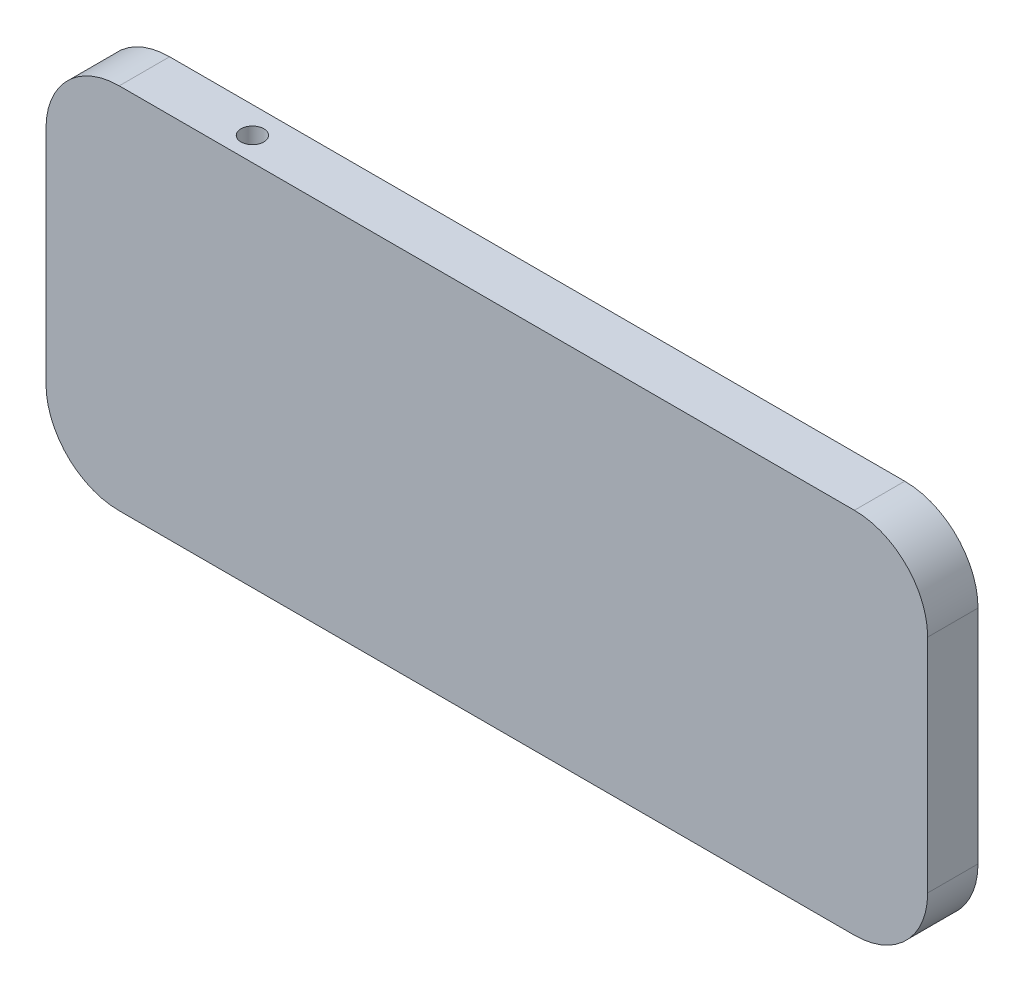
SolidWorks part; units mm, degrees
ref_plane "Front Plane" through (0, 0, 0) normal (0, 0, 1) x (1, 0, 0)
ref_plane "Top Plane" through (0, 0, 0) normal (0, 1, 0) x (1, 0, 0)
ref_plane "Right Plane" through (0, 0, 0) normal (1, 0, 0) x (0, 0, -1)
sketch "Sketch1" plane through (0, 0, 0) normal (0, 0, 1) x (1, 0, 0)
  line L1 (-43.0173, 84.2239) -> (160.9447, 84.2239)
  line L2 (-63.3373, 63.9039) -> (-63.3373, 2.4359)
  line L3 (-43.0173, -17.8841) -> (160.9447, -17.8841)
  line L4 (181.2647, 63.9039) -> (181.2647, 2.4359)
  line L5 (-27.5233, 84.2239) -> (-27.5233, -17.8841)
  line L7 (145.4507, 84.2239) -> (145.4507, -17.8841)
  arc A0 (-63.3373, 63.9039) -> (-43.0173, 84.2239) centre (-43.0173, 63.9039) cw
  arc A1 (-63.3373, 2.4359) -> (-43.0173, -17.8841) centre (-43.0173, 2.4359) ccw
  arc A2 (181.2647, 63.9039) -> (160.9447, 84.2239) centre (160.9447, 63.9039) ccw
  arc A3 (160.9447, -17.8841) -> (181.2647, 2.4359) centre (160.9447, 2.4359) ccw
  point P10 (-63.3373, 84.2239)
  point P13 (-63.3373, -17.8841)
  point P16 (181.2647, 84.2239)
  dimension "D5" = 20.32
  dimension "D6" = 20.32
  dimension "D7" = 20.32
  dimension "D8" = 20.32
  dimension "D1" = 244.602
  dimension "D2" = 102.108
  dimension "D3" = 35.814
  dimension "D4" = 35.814
extrude "Boss-Extrude1" add sketch "Sketch1" along normal blind 13.97 contours L7 L1 L5 L3 | L2 A1 L3 L5 L1 A0 | L3 A3 L4 A2 L1 L7
sketch "Sketch2" plane through (0, 0, 0) normal (0, 0, -1) x (-1, 0, 0)
  line L0 (-145.4507, 84.2239) -> (-145.4507, -17.8841)
  line L1 (43.0173, 84.2239) -> (-160.9447, 84.2239) construction
  line L2 (43.0173, -17.8841) -> (-160.9447, -17.8841) construction
  line L3 (-181.2647, 63.9039) -> (-181.2647, 2.4359) construction
  line L5 (-156.6365, 76.06) -> (-148.8243, 76.06)
  line L6 (-156.6365, 76.06) -> (-156.6365, 73.6521)
  line L7 (-156.6365, 73.6521) -> (-148.8243, 73.6521)
  line L8 (-148.8243, 76.06) -> (-148.8243, 73.6521)
  circle A0 centre (-163.4847, 58.8239) radius 7.4676
  circle A1 centre (-170.3371, 26.676) radius 3.015
  circle A2 centre (-163.2212, 32.8237) radius 3.015
  circle A3 centre (-156.7324, 26.2052) radius 3.015
  circle A4 centre (-163.7215, 19.9736) radius 3.015
  dimension "D2" = 17.78
  dimension "D1" = 35.814
  dimension "D3" = 25.4
extrude "Boss-Extrude3" add sketch "Sketch2" along normal blind 3.048 contours A3 | A2 | A4 | A1 | A0 | L6 L7 L8 L5
sketch "Sketch3" plane through (0, 0, 0) normal (0, 0, -1) x (-1, 0, 0)
  line L0 (27.7773, 84.2239) -> (27.7773, -17.8841)
  line L1 (43.0173, 84.2239) -> (-160.9447, 84.2239) construction
  line L2 (43.0173, -17.8841) -> (-160.9447, -17.8841) construction
  line L3 (63.3373, 63.9039) -> (63.3373, 2.4359) construction
  line L4 (35.9334, 76.3914) -> (35.9334, 78.9314)
  line L6 (33.5703, 76.3914) -> (33.5703, 73.9836)
  line L8 (41.1903, 76.3914) -> (41.1903, 73.9836)
  line L9 (35.9334, 78.9314) -> (38.4734, 78.9314)
  line L10 (38.4734, 76.3914) -> (38.4734, 78.9314)
  line L11 (38.4734, 73.9836) -> (38.4734, 71.4436)
  line L12 (38.4734, 71.4436) -> (35.9334, 71.4436)
  line L13 (35.9334, 71.4436) -> (35.9334, 73.9836)
  line L14 (41.1903, 73.9836) -> (38.4734, 73.9836)
  line L15 (33.5703, 73.9836) -> (35.9334, 73.9836)
  line L16 (33.5703, 76.3914) -> (35.9334, 76.3914)
  line L17 (38.4734, 76.3914) -> (41.1903, 76.3914)
  circle A0 centre (45.4875, 28.5164) radius 7.4676
  circle A1 centre (38.3418, 59.8184) radius 3.015
  circle A2 centre (45.4577, 65.9661) radius 3.015
  circle A3 centre (51.9466, 59.3476) radius 3.015
  circle A4 centre (44.9575, 53.1161) radius 3.015
  dimension "D1" = 35.56
extrude "Boss-Extrude5" add sketch "Sketch3" along normal blind 3.048 contours A0 | A4 | A1 | A2 | A3 | L17 L10 L9 L4 L16 L6 L15 L13 L12 L11 L14 L8
sketch "Sketch4" plane through (0, 84.2239, 0) normal (0, 1, 0) x (1, 0, 0)
  circle A0 centre (-12.6411, -7.4001) radius 3.175
  point P2 (-33.9493, -8.0906)
extrude "Cut-Extrude1" cut sketch "Sketch4" against normal blind 11.176 contours A0
